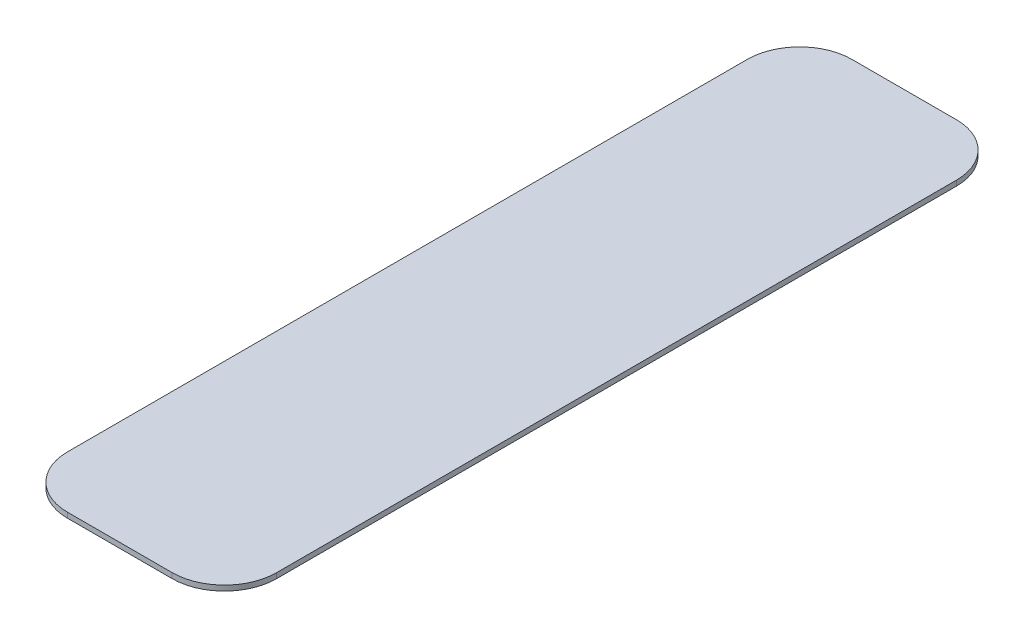
SolidWorks part; units mm, degrees
material "Nickel"
ref_plane "Front" through (0, 0, 0) normal (0, 0, 1) x (1, 0, 0)
ref_plane "Top" through (0, 0, 0) normal (0, 1, 0) x (1, 0, 0)
ref_plane "Right" through (0, 0, 0) normal (1, 0, 0) x (0, 0, -1)
sketch "Sketch1" plane through (0, 0, 0) normal (0, 0, 1) x (1, 0, 0)
  line L1 (-4, 0.1) -> (4, 0.1)
  line L2 (-4, 0.1) -> (-4, -0.1)
  line L3 (-4, -0.1) -> (4, -0.1)
  line L4 (4, 0.1) -> (4, -0.1)
  line L5 (-4, 0.1) -> (4, -0.1) construction
  line L6 (-4, -0.1) -> (4, 0.1) construction
  point P4 (0, 0)
  dimension "D1" = 8
  dimension "D2" = 0.2
extrude "Boss-Extrude1" add sketch "Sketch1" along normal mid plane 30
fillet "Fillet1" radius 2 4 edges at (4, 0, -15) (-4, 0, -15) (-4, 0, 15) (4, 0, 15)
